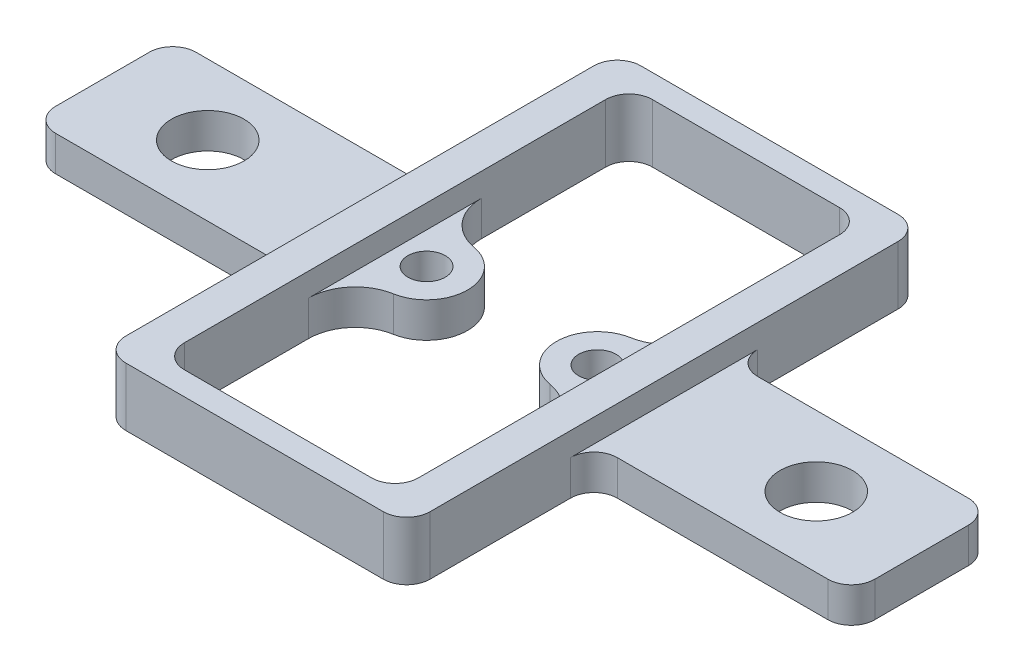
SolidWorks part; units mm, degrees
material "ABS"
ref_plane "前视基准面" through (0, 0, 0) normal (0, 0, 1) x (1, 0, 0)
ref_plane "上视基准面" through (0, 0, 0) normal (0, 1, 0) x (1, 0, 0)
ref_plane "右视基准面" through (0, 0, 0) normal (1, 0, 0) x (0, 0, -1)
sketch "草图1" plane through (0, 0, 0) normal (0, 1, 0) x (1, 0, 0)
  line L1 (-6.5, -11) -> (6.5, -11)
  line L2 (-6.5, -11) -> (-6.5, 11)
  line L3 (-6.5, 11) -> (6.5, 11)
  line L4 (6.5, -11) -> (6.5, 11)
  line L5 (-6.5, -11) -> (6.5, 11) construction
  line L6 (-6.5, 11) -> (6.5, -11) construction
  line L7 (-17.5, -3) -> (17.5, -3)
  line L8 (-17.5, -3) -> (-17.5, 3)
  line L9 (-17.5, 3) -> (17.5, 3)
  line L10 (17.5, -3) -> (17.5, 3)
  line L11 (-17.5, -3) -> (17.5, 3) construction
  line L12 (-17.5, 3) -> (17.5, -3) construction
  point P0 (0, 0)
  point P6 (0, 0)
  dimension "D1" = 13
  dimension "D2" = 22
  dimension "D3" = 6
  dimension "D4" = 35
extrude "凸台-拉伸1" add sketch "草图1" along normal blind 1.5 contours L9 L8 L7 L2 | L7 L2 L1 L4 | L9 L2 L7 L4 | L2 L9 L4 L3 | L7 L10 L9 L4
sketch "草图2" plane through (0, 1.5, 0) normal (0, 1, 0) x (1, 0, 0)
  line L0 (0, 0) -> (-3.65, 0) construction
  line L1 (-5, -10) -> (5, -10)
  line L2 (-5, -10) -> (-5, -1.1136)
  line L3 (-5, 10) -> (5, 10)
  line L4 (5, -10) -> (5, -1.1136)
  line L5 (-5, -10) -> (5, 10) construction
  line L6 (-5, 10) -> (5, -10) construction
  line L7 (-5, 1.1136) -> (-5, 10)
  line L8 (0, 0) -> (0, -10) construction
  line L9 (5, 1.1136) -> (5, 10)
  arc A1 (-5, -1.1136) -> (-5, 1.1136) centre (-3.65, 0) ccw
  arc A2 (5, -1.1136) -> (5, 1.1136) centre (3.65, 0) cw
  point P0 (0, 0)
  dimension "D3" = 3.65
  dimension "D4" = 3.5
  dimension "D1" = 10
  dimension "D2" = 20
extrude "切除-拉伸1" cut sketch "草图2" against normal blind 1.5
fillet "圆角1" radius 2 4 edges at (5, 0.75, -1.1136) (5, 0.75, 1.1136) (-5, 0.75, 1.1136) (-5, 0.75, -1.1136)
fillet "圆角2" radius 1 16 edges at (-17.5, 0.75, -3) (-17.5, 0.75, 3) (-6.5, 0.75, 3) (-6.5, 0.75, 11) (6.5, 0.75, 11) (6.5, 0.75, 3) (17.5, 0.75, 3) (17.5, 0.75, -3) (6.5, 0.75, -3) (6.5, 0.75, -11) (-6.5, 0.75, -11) (-6.5, 0.75, -3) (5, 0.75, 10) (-5, 0.75, 10) (5, 0.75, -10) (-5, 0.75, -10)
sketch "草图3" plane through (0, 1.5, 0) normal (0, 1, 0) x (1, 0, 0)
  line L0 (0, 0) -> (0, 4.3185) construction
  circle A0 centre (-3.65, 0) radius 0.8
  circle A1 centre (3.65, 0) radius 0.8
  dimension "D1" = 1.6
extrude "切除-拉伸2" cut sketch "草图3" against normal blind 10
sketch "草图4" plane through (0, 1.5, 0) normal (0, 1, 0) x (1, 0, 0)
  line L0 (-6.5, -4) -> (-6.5, 4)
  line L2 (6.5, -4) -> (6.5, 4)
  line L3 (-5, 9) -> (-5, 3.6932) construction
  line L4 (4, 10) -> (-4, 10) construction
  line L5 (5, 3.6932) -> (5, 9) construction
  line L6 (5, -9) -> (5, -3.6932) construction
  line L7 (-4, -10) -> (4, -10) construction
  line L8 (-5, -3.6932) -> (-5, -9) construction
  line L9 (5, -3.6932) -> (5, 9)
  line L10 (5, -9) -> (5, -3.6932)
  line L11 (-4, -10) -> (4, -10)
  line L12 (-5, -3.6932) -> (-5, -9)
  line L13 (-17.5, 2) -> (-17.5, -2)
  line L14 (-7.5, 3) -> (-16.5, 3)
  line L15 (-6.5, 10) -> (-6.5, 4)
  line L16 (5.5, 11) -> (-5.5, 11)
  line L17 (6.5, 4) -> (6.5, 10)
  line L18 (16.5, 3) -> (7.5, 3)
  line L19 (17.5, -2) -> (17.5, 2)
  line L20 (7.5, -3) -> (16.5, -3)
  line L21 (6.5, -10) -> (6.5, -4)
  line L22 (-5.5, -11) -> (5.5, -11)
  line L23 (-6.5, -4) -> (-6.5, -10)
  line L24 (-16.5, -3) -> (-7.5, -3)
  line L27 (-6.5, 10) -> (-6.5, 4)
  line L28 (5.5, 11) -> (-5.5, 11)
  line L29 (6.5, 4) -> (6.5, 10)
  line L33 (6.5, -10) -> (6.5, -4)
  line L34 (-5.5, -11) -> (5.5, -11)
  line L35 (-6.5, -4) -> (-6.5, -10)
  line L37 (-5, 9) -> (-5, -3.6932)
  line L38 (4, 10) -> (-4, 10)
  arc A0 (-4, 10) -> (-5, 9) centre (-4, 9) ccw construction
  arc A4 (4, -10) -> (5, -9) centre (4, -9) ccw construction
  arc A5 (-5, -9) -> (-4, -10) centre (-4, -9) ccw construction
  arc A9 (5, 9) -> (4, 10) centre (4, 9) ccw construction
  arc A12 (-16.5, 3) -> (-17.5, 2) centre (-16.5, 2) ccw
  arc A13 (-7.5, 3) -> (-6.5, 4) centre (-7.5, 4) ccw
  arc A14 (-5.5, 11) -> (-6.5, 10) centre (-5.5, 10) ccw
  arc A15 (6.5, 10) -> (5.5, 11) centre (5.5, 10) ccw
  arc A16 (6.5, 4) -> (7.5, 3) centre (7.5, 4) ccw
  arc A17 (17.5, 2) -> (16.5, 3) centre (16.5, 2) ccw
  arc A18 (16.5, -3) -> (17.5, -2) centre (16.5, -2) ccw
  arc A19 (7.5, -3) -> (6.5, -4) centre (7.5, -4) ccw
  arc A20 (5.5, -11) -> (6.5, -10) centre (5.5, -10) ccw
  arc A21 (-6.5, -10) -> (-5.5, -11) centre (-5.5, -10) ccw
  arc A22 (-6.5, -4) -> (-7.5, -3) centre (-7.5, -4) ccw
  arc A23 (-17.5, -2) -> (-16.5, -3) centre (-16.5, -2) ccw
  arc A26 (-5.5, 11) -> (-6.5, 10) centre (-5.5, 10) ccw
  arc A27 (6.5, 10) -> (5.5, 11) centre (5.5, 10) ccw
  arc A32 (5.5, -11) -> (6.5, -10) centre (5.5, -10) ccw
  arc A33 (-6.5, -10) -> (-5.5, -11) centre (-5.5, -10) ccw
  arc A37 (4, -10) -> (5, -9) centre (4, -9) ccw
  arc A38 (-5, -9) -> (-4, -10) centre (-4, -9) ccw
  arc A42 (-4, 10) -> (-5, 9) centre (-4, 9) ccw
  arc A43 (5, 9) -> (4, 10) centre (4, 9) ccw
  dimension "D1" = 0
extrude "凸台-拉伸2" add sketch "草图4" along normal blind 1
sketch "草图5" plane through (0, 0, 0) normal (0, -1, 0) x (1, 0, 0)
  line L0 (-17.5, 0) -> (17.5, 0) construction
  line L1 (-17.5, 2) -> (-17.5, -2) construction
  line L2 (17.5, 2) -> (17.5, -2) construction
  line L3 (0, 0) -> (0, -10) construction
  line L4 (4, -10) -> (-4, -10) construction
  circle A0 centre (-13, 0) radius 1.55
  circle A1 centre (13, 0) radius 1.55
  dimension "D1" = 3.1
  dimension "D2" = 26
extrude "切除-拉伸3" cut sketch "草图5" against normal blind 10
